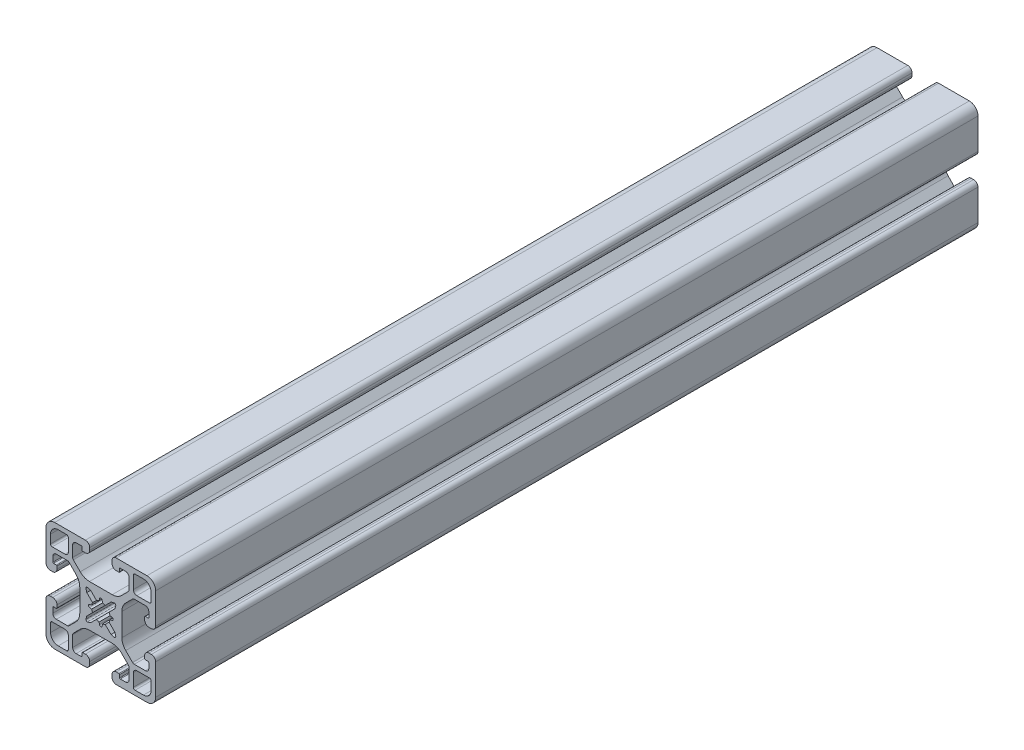
SolidWorks part; units mm, degrees
other "Extrude1"
material "6105-T5 Aluminum"
ref_plane "Front Plane" through (0, 0, 0) normal (0, 0, 1) x (1, 0, 0)
ref_plane "Top Plane" through (0, 0, 0) normal (0, 1, 0) x (1, 0, 0)
ref_plane "Right Plane" through (0, 0, 0) normal (1, 0, 0) x (0, 0, -1)
sketch "Sketch1" plane through (0, 0, 0) normal (0, 0, 1) x (1, 0, 0)
  line L0 (12.4898, -18.345) -> (15.545, -18.345)
  line L1 (11.8598, -13.1298) -> (11.8598, -17.715)
  line L2 (17.715, -11.8598) -> (13.1298, -11.8598)
  line L3 (18.345, -15.545) -> (18.345, -12.4898)
  line L4 (-18.345, -12.4898) -> (-18.345, -15.545)
  line L5 (-13.1298, -11.8598) -> (-17.715, -11.8598)
  line L6 (-11.8598, -17.715) -> (-11.8598, -13.1298)
  line L7 (-15.545, -18.345) -> (-12.4898, -18.345)
  line L8 (18.345, 12.4898) -> (18.345, 15.545)
  line L9 (13.1298, 11.8598) -> (17.715, 11.8598)
  line L10 (11.8598, 17.715) -> (11.8598, 13.1298)
  line L11 (15.545, 18.345) -> (12.4898, 18.345)
  line L12 (-12.4898, 18.345) -> (-15.545, 18.345)
  line L13 (-11.8598, 13.1298) -> (-11.8598, 17.715)
  line L14 (-17.715, 11.8598) -> (-13.1298, 11.8598)
  line L15 (-18.345, 15.545) -> (-18.345, 12.4898)
  line L16 (-5.63, 20) -> (-16.83, 20)
  line L17 (-20, 16.83) -> (-20, 5.63)
  line L18 (-18.43, 4.06) -> (-17.57, 4.06)
  line L19 (-16, 5.63) -> (-16, 6.605)
  line L20 (-16.25, 6.855) -> (-17.25, 6.855)
  line L21 (-17.5, 7.105) -> (-17.5, 9.015)
  line L22 (-16.23, 10.285) -> (-12.2162, 10.285)
  line L23 (-11.5869, 10.0243) -> (-9.0762, 7.5137)
  line L24 (-7.685, 4.1549) -> (-7.685, -4.1549)
  line L25 (-9.0762, -7.5137) -> (-11.5869, -10.0243)
  line L26 (-12.2162, -10.285) -> (-16.23, -10.285)
  line L27 (-17.5, -9.015) -> (-17.5, -7.105)
  line L28 (-17.25, -6.855) -> (-16.25, -6.855)
  line L29 (-16, -6.605) -> (-16, -5.63)
  line L30 (-17.57, -4.06) -> (-18.43, -4.06)
  line L31 (-20, -5.63) -> (-20, -16.83)
  line L32 (-16.83, -20) -> (-5.63, -20)
  line L33 (-4.06, -18.43) -> (-4.06, -17.57)
  line L34 (-5.63, -16) -> (-6.605, -16)
  line L35 (-6.855, -16.25) -> (-6.855, -17.25)
  line L36 (-7.105, -17.5) -> (-9.015, -17.5)
  line L37 (-10.285, -16.23) -> (-10.285, -12.2162)
  line L38 (-10.0243, -11.5869) -> (-7.5137, -9.0762)
  line L39 (-4.1549, -7.685) -> (4.1549, -7.685)
  line L40 (7.5137, -9.0762) -> (10.0243, -11.5869)
  line L41 (10.285, -12.2162) -> (10.285, -16.23)
  line L42 (9.015, -17.5) -> (7.105, -17.5)
  line L43 (6.855, -17.25) -> (6.855, -16.25)
  line L44 (6.605, -16) -> (5.63, -16)
  line L45 (4.06, -17.57) -> (4.06, -18.43)
  line L46 (5.63, -20) -> (16.83, -20)
  line L47 (20, -16.83) -> (20, -5.63)
  line L48 (18.43, -4.06) -> (17.57, -4.06)
  line L49 (16, -5.63) -> (16, -6.605)
  line L50 (16.25, -6.855) -> (17.25, -6.855)
  line L51 (17.5, -7.105) -> (17.5, -9.015)
  line L52 (16.23, -10.285) -> (12.2162, -10.285)
  line L53 (11.5869, -10.0243) -> (9.0762, -7.5137)
  line L54 (7.685, -4.1549) -> (7.685, 4.1549)
  line L55 (9.0762, 7.5137) -> (11.5869, 10.0243)
  line L56 (12.2162, 10.285) -> (16.23, 10.285)
  line L57 (17.5, 9.015) -> (17.5, 7.105)
  line L58 (17.25, 6.855) -> (16.25, 6.855)
  line L59 (16, 6.605) -> (16, 5.63)
  line L60 (17.57, 4.06) -> (18.43, 4.06)
  line L61 (20, 5.63) -> (20, 16.83)
  line L62 (16.83, 20) -> (5.63, 20)
  line L63 (4.06, 18.43) -> (4.06, 17.57)
  line L64 (5.63, 16) -> (6.605, 16)
  line L65 (6.855, 16.25) -> (6.855, 17.25)
  line L66 (7.105, 17.5) -> (9.015, 17.5)
  line L67 (10.285, 16.23) -> (10.285, 12.2162)
  line L68 (10.0243, 11.5869) -> (7.5137, 9.0762)
  line L69 (4.1549, 7.685) -> (-4.1549, 7.685)
  line L70 (-7.5137, 9.0762) -> (-10.0243, 11.5869)
  line L71 (-10.285, 12.2162) -> (-10.285, 16.23)
  line L72 (-9.015, 17.5) -> (-7.105, 17.5)
  line L73 (-6.855, 17.25) -> (-6.855, 16.25)
  line L74 (-6.605, 16) -> (-5.63, 16)
  line L75 (-4.06, 17.57) -> (-4.06, 18.43)
  line L76 (-4.8481, -5.4393) -> (-3.712, -5.1263)
  line L77 (-3.712, -5.1263) -> (-1.5907, -3.0049)
  line L78 (-0.625, -3.3421) -> (-0.4923, -4.0876)
  line L79 (0.4923, -4.0876) -> (0.625, -3.3421)
  line L80 (1.5907, -3.0049) -> (3.712, -5.1263)
  line L81 (3.712, -5.1263) -> (4.8481, -5.4393)
  line L82 (5.4393, -4.8481) -> (5.1263, -3.712)
  line L83 (5.1263, -3.712) -> (3.0049, -1.5907)
  line L84 (3.3421, -0.625) -> (4.0876, -0.4923)
  line L85 (4.0876, 0.4923) -> (3.3421, 0.625)
  line L86 (3.0049, 1.5907) -> (5.1263, 3.712)
  line L87 (5.1263, 3.712) -> (5.4393, 4.8481)
  line L88 (4.8481, 5.4393) -> (3.712, 5.1263)
  line L89 (3.712, 5.1263) -> (1.5907, 3.0049)
  line L90 (0.625, 3.3421) -> (0.4923, 4.0876)
  line L91 (-0.4923, 4.0876) -> (-0.625, 3.3421)
  line L92 (-1.5907, 3.0049) -> (-3.712, 5.1263)
  line L93 (-3.712, 5.1263) -> (-4.8481, 5.4393)
  line L94 (-5.4393, 4.8481) -> (-5.1263, 3.712)
  line L95 (-5.1263, 3.712) -> (-3.0049, 1.5907)
  line L96 (-3.3421, 0.625) -> (-4.0876, 0.4923)
  line L97 (-4.0876, -0.4923) -> (-3.3421, -0.625)
  line L98 (-3.0049, -1.5907) -> (-5.1263, -3.712)
  line L99 (-5.1263, -3.712) -> (-5.4393, -4.8481)
  arc A0 (15.545, -18.345) -> (18.345, -15.545) centre (15.545, -15.545) ccw
  arc A1 (11.8598, -17.715) -> (12.4898, -18.345) centre (12.4898, -17.715) ccw
  arc A2 (13.1298, -11.8598) -> (11.8598, -13.1298) centre (13.1298, -13.1298) ccw
  arc A3 (18.345, -12.4898) -> (17.715, -11.8598) centre (17.715, -12.4898) ccw
  arc A4 (-18.345, -15.545) -> (-15.545, -18.345) centre (-15.545, -15.545) ccw
  arc A5 (-17.715, -11.8598) -> (-18.345, -12.4898) centre (-17.715, -12.4898) ccw
  arc A6 (-11.8598, -13.1298) -> (-13.1298, -11.8598) centre (-13.1298, -13.1298) ccw
  arc A7 (-12.4898, -18.345) -> (-11.8598, -17.715) centre (-12.4898, -17.715) ccw
  arc A8 (18.345, 15.545) -> (15.545, 18.345) centre (15.545, 15.545) ccw
  arc A9 (17.715, 11.8598) -> (18.345, 12.4898) centre (17.715, 12.4898) ccw
  arc A10 (11.8598, 13.1298) -> (13.1298, 11.8598) centre (13.1298, 13.1298) ccw
  arc A11 (12.4898, 18.345) -> (11.8598, 17.715) centre (12.4898, 17.715) ccw
  arc A12 (-15.545, 18.345) -> (-18.345, 15.545) centre (-15.545, 15.545) ccw
  arc A13 (-11.8598, 17.715) -> (-12.4898, 18.345) centre (-12.4898, 17.715) ccw
  arc A14 (-13.1298, 11.8598) -> (-11.8598, 13.1298) centre (-13.1298, 13.1298) ccw
  arc A15 (-18.345, 12.4898) -> (-17.715, 11.8598) centre (-17.715, 12.4898) ccw
  arc A16 (-4.06, 18.43) -> (-5.63, 20) centre (-5.63, 18.43) ccw
  arc A17 (-16.83, 20) -> (-20, 16.83) centre (-16.83, 16.83) ccw
  arc A18 (-20, 5.63) -> (-18.43, 4.06) centre (-18.43, 5.63) ccw
  arc A19 (-17.57, 4.06) -> (-16, 5.63) centre (-17.57, 5.63) ccw
  arc A20 (-16, 6.605) -> (-16.25, 6.855) centre (-16.25, 6.605) ccw
  arc A21 (-17.5, 7.105) -> (-17.25, 6.855) centre (-17.25, 7.105) ccw
  arc A22 (-16.23, 10.285) -> (-17.5, 9.015) centre (-16.23, 9.015) ccw
  arc A23 (-11.5869, 10.0243) -> (-12.2162, 10.285) centre (-12.2162, 9.395) ccw
  arc A24 (-7.685, 4.1549) -> (-9.0762, 7.5137) centre (-12.435, 4.1549) ccw
  arc A25 (-9.0762, -7.5137) -> (-7.685, -4.1549) centre (-12.435, -4.1549) ccw
  arc A26 (-12.2162, -10.285) -> (-11.5869, -10.0243) centre (-12.2162, -9.395) ccw
  arc A27 (-17.5, -9.015) -> (-16.23, -10.285) centre (-16.23, -9.015) ccw
  arc A28 (-17.25, -6.855) -> (-17.5, -7.105) centre (-17.25, -7.105) ccw
  arc A29 (-16.25, -6.855) -> (-16, -6.605) centre (-16.25, -6.605) ccw
  arc A30 (-16, -5.63) -> (-17.57, -4.06) centre (-17.57, -5.63) ccw
  arc A31 (-18.43, -4.06) -> (-20, -5.63) centre (-18.43, -5.63) ccw
  arc A32 (-20, -16.83) -> (-16.83, -20) centre (-16.83, -16.83) ccw
  arc A33 (-5.63, -20) -> (-4.06, -18.43) centre (-5.63, -18.43) ccw
  arc A34 (-4.06, -17.57) -> (-5.63, -16) centre (-5.63, -17.57) ccw
  arc A35 (-6.605, -16) -> (-6.855, -16.25) centre (-6.605, -16.25) ccw
  arc A36 (-7.105, -17.5) -> (-6.855, -17.25) centre (-7.105, -17.25) ccw
  arc A37 (-10.285, -16.23) -> (-9.015, -17.5) centre (-9.015, -16.23) ccw
  arc A38 (-10.0243, -11.5869) -> (-10.285, -12.2162) centre (-9.395, -12.2162) ccw
  arc A39 (-4.1549, -7.685) -> (-7.5137, -9.0762) centre (-4.1549, -12.435) ccw
  arc A40 (7.5137, -9.0762) -> (4.1549, -7.685) centre (4.1549, -12.435) ccw
  arc A41 (10.285, -12.2162) -> (10.0243, -11.5869) centre (9.395, -12.2162) ccw
  arc A42 (9.015, -17.5) -> (10.285, -16.23) centre (9.015, -16.23) ccw
  arc A43 (6.855, -17.25) -> (7.105, -17.5) centre (7.105, -17.25) ccw
  arc A44 (6.855, -16.25) -> (6.605, -16) centre (6.605, -16.25) ccw
  arc A45 (5.63, -16) -> (4.06, -17.57) centre (5.63, -17.57) ccw
  arc A46 (4.06, -18.43) -> (5.63, -20) centre (5.63, -18.43) ccw
  arc A47 (16.83, -20) -> (20, -16.83) centre (16.83, -16.83) ccw
  arc A48 (20, -5.63) -> (18.43, -4.06) centre (18.43, -5.63) ccw
  arc A49 (17.57, -4.06) -> (16, -5.63) centre (17.57, -5.63) ccw
  arc A50 (16, -6.605) -> (16.25, -6.855) centre (16.25, -6.605) ccw
  arc A51 (17.5, -7.105) -> (17.25, -6.855) centre (17.25, -7.105) ccw
  arc A52 (16.23, -10.285) -> (17.5, -9.015) centre (16.23, -9.015) ccw
  arc A53 (11.5869, -10.0243) -> (12.2162, -10.285) centre (12.2162, -9.395) ccw
  arc A54 (7.685, -4.1549) -> (9.0762, -7.5137) centre (12.435, -4.1549) ccw
  arc A55 (9.0762, 7.5137) -> (7.685, 4.1549) centre (12.435, 4.1549) ccw
  arc A56 (12.2162, 10.285) -> (11.5869, 10.0243) centre (12.2162, 9.395) ccw
  arc A57 (17.5, 9.015) -> (16.23, 10.285) centre (16.23, 9.015) ccw
  arc A58 (17.25, 6.855) -> (17.5, 7.105) centre (17.25, 7.105) ccw
  arc A59 (16.25, 6.855) -> (16, 6.605) centre (16.25, 6.605) ccw
  arc A60 (16, 5.63) -> (17.57, 4.06) centre (17.57, 5.63) ccw
  arc A61 (18.43, 4.06) -> (20, 5.63) centre (18.43, 5.63) ccw
  arc A62 (20, 16.83) -> (16.83, 20) centre (16.83, 16.83) ccw
  arc A63 (5.63, 20) -> (4.06, 18.43) centre (5.63, 18.43) ccw
  arc A64 (4.06, 17.57) -> (5.63, 16) centre (5.63, 17.57) ccw
  arc A65 (6.605, 16) -> (6.855, 16.25) centre (6.605, 16.25) ccw
  arc A66 (7.105, 17.5) -> (6.855, 17.25) centre (7.105, 17.25) ccw
  arc A67 (10.285, 16.23) -> (9.015, 17.5) centre (9.015, 16.23) ccw
  arc A68 (10.0243, 11.5869) -> (10.285, 12.2162) centre (9.395, 12.2162) ccw
  arc A69 (4.1549, 7.685) -> (7.5137, 9.0762) centre (4.1549, 12.435) ccw
  arc A70 (-7.5137, 9.0762) -> (-4.1549, 7.685) centre (-4.1549, 12.435) ccw
  arc A71 (-10.285, 12.2162) -> (-10.0243, 11.5869) centre (-9.395, 12.2162) ccw
  arc A72 (-9.015, 17.5) -> (-10.285, 16.23) centre (-9.015, 16.23) ccw
  arc A73 (-6.855, 17.25) -> (-7.105, 17.5) centre (-7.105, 17.25) ccw
  arc A74 (-6.855, 16.25) -> (-6.605, 16) centre (-6.605, 16.25) ccw
  arc A75 (-5.63, 16) -> (-4.06, 17.57) centre (-5.63, 17.57) ccw
  arc A76 (-1.5907, -3.0049) -> (-0.625, -3.3421) centre (0, 0) ccw
  arc A77 (-0.4923, -4.0876) -> (0.4923, -4.0876) centre (0, -4) ccw
  arc A78 (0.625, -3.3421) -> (1.5907, -3.0049) centre (0, 0) ccw
  arc A79 (4.8481, -5.4393) -> (5.4393, -4.8481) centre (4.9497, -4.9497) ccw
  arc A80 (3.0049, -1.5907) -> (3.3421, -0.625) centre (0, 0) ccw
  arc A81 (4.0876, -0.4923) -> (4.0876, 0.4923) centre (4, 0) ccw
  arc A82 (3.3421, 0.625) -> (3.0049, 1.5907) centre (0, 0) ccw
  arc A83 (5.4393, 4.8481) -> (4.8481, 5.4393) centre (4.9497, 4.9497) ccw
  arc A84 (1.5907, 3.0049) -> (0.625, 3.3421) centre (0, 0) ccw
  arc A85 (0.4923, 4.0876) -> (-0.4923, 4.0876) centre (0, 4) ccw
  arc A86 (-0.625, 3.3421) -> (-1.5907, 3.0049) centre (0, 0) ccw
  arc A87 (-4.8481, 5.4393) -> (-5.4393, 4.8481) centre (-4.9497, 4.9497) ccw
  arc A88 (-3.0049, 1.5907) -> (-3.3421, 0.625) centre (0, 0) ccw
  arc A89 (-4.0876, 0.4923) -> (-4.0876, -0.4923) centre (-4, 0) ccw
  arc A90 (-3.3421, -0.625) -> (-3.0049, -1.5907) centre (0, 0) ccw
  arc A91 (-5.4393, -4.8481) -> (-4.8481, -5.4393) centre (-4.9497, -4.9497) ccw
extrude "Extrude1" add sketch "Sketch1" against normal blind 300
